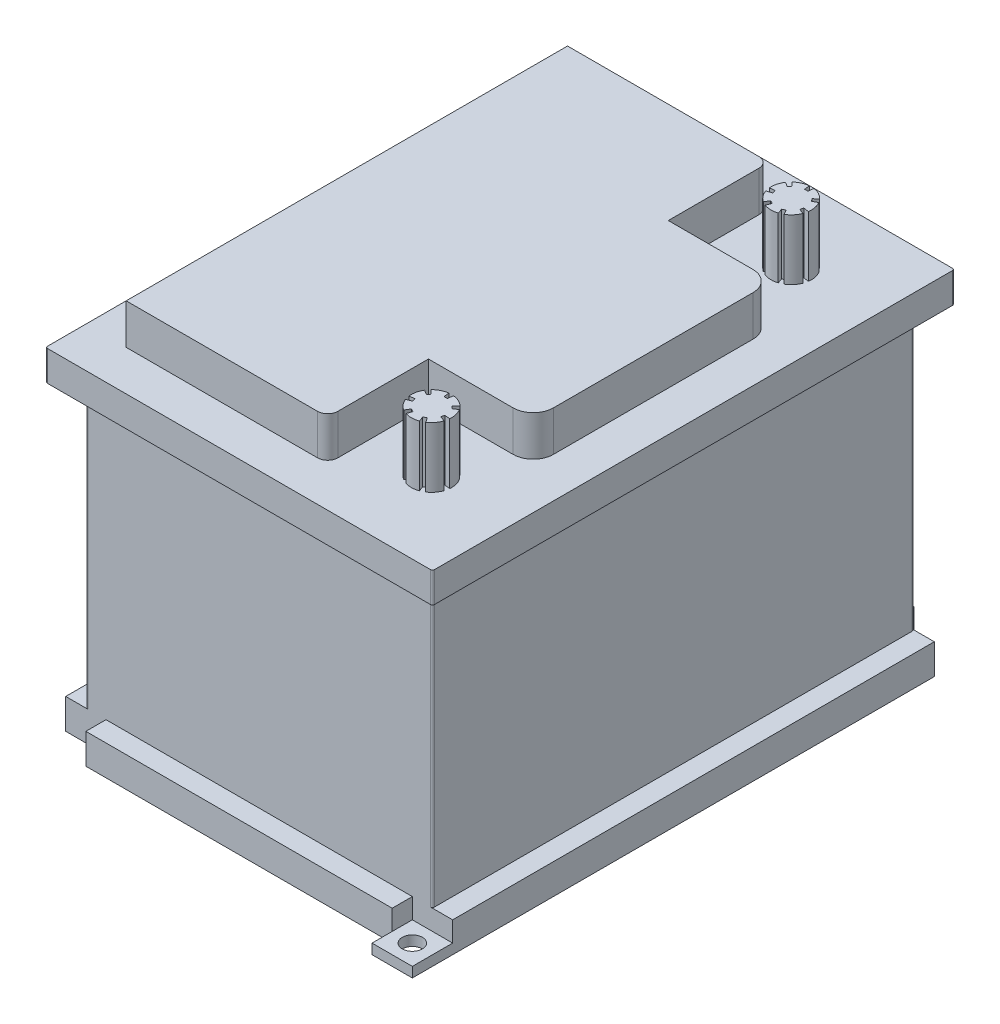
SolidWorks part; units mm, degrees
ref_plane "Front Plane" through (0, 0, 0) normal (0, 0, 1) x (1, 0, 0)
ref_plane "Top Plane" through (0, 0, 0) normal (0, 1, 0) x (1, 0, 0)
ref_plane "Right Plane" through (0, 0, 0) normal (1, 0, 0) x (0, 0, -1)
sketch "Sketch1" plane through (0, 0, 0) normal (0, 1, 0) x (1, 0, 0)
  line L3 (30.4274, 35.6969) -> (202.4274, 35.6969)
  line L4 (30.4274, 35.6969) -> (30.4274, -203.3031)
  line L5 (30.4274, -203.3031) -> (202.4274, -203.3031)
  line L6 (202.4274, 35.6969) -> (202.4274, -203.3031)
extrude "Boss-Extrude1" add sketch "Sketch1" along normal blind 190
sketch "Sketch2" plane through (0, 190, 0) normal (0, 1, 0) x (1, 0, 0)
  line L0 (192.4274, 35.6969) -> (40.4274, 35.6969)
  line L5 (202.4274, 35.6969) -> (30.4274, 35.6969) construction
  line L6 (30.4274, -193.3031) -> (30.4274, -203.3031)
  line L13 (40.4274, 25.6969) -> (192.4274, 25.6969)
  line L14 (40.4274, 25.6969) -> (40.4274, -193.3031)
  line L15 (40.4274, -193.3031) -> (192.4274, -193.3031)
  line L16 (192.4274, 25.6969) -> (192.4274, -193.3031)
  line L17 (30.4274, 35.6969) -> (202.4274, 35.6969)
  line L18 (30.4274, 35.6969) -> (30.4274, -203.3031)
  line L19 (30.4274, -203.3031) -> (202.4274, -203.3031)
  line L20 (202.4274, 35.6969) -> (202.4274, -203.3031)
  point P5 (116.4274, 35.6969)
  point P10 (30.4274, -198.3031)
  line M11 (30.4274, 35.6969) -> (30.4274, -203.3031)
  line M12 (30.4274, -203.3031) -> (202.4274, -203.3031)
  line M13 (202.4274, -203.3031) -> (202.4274, 35.6969)
  line M14 (202.4274, 35.6969) -> (30.4274, 35.6969)
extrude "Cut-Extrude1" cut sketch "Sketch2" against normal blind 20 contours L13 L16 L15 L14 M14 M11 M12 M13
sketch "Sketch3" plane through (0, 190, 0) normal (0, 1, 0) x (1, 0, 0)
  line L0 (40.4274, -193.3031) -> (192.4274, -193.3031) construction
  line L1 (40.4274, 25.6969) -> (140.4274, 25.6969) construction
  line L2 (40.4274, 25.6969) -> (40.4274, -193.3031) construction
  line L3 (40.4274, -193.3031) -> (140.4274, -193.3031) construction
  line L4 (140.4274, 25.6969) -> (140.4274, -193.3031) construction
  line L5 (140.4274, 25.6969) -> (140.4274, -24.3031)
  line L6 (140.4274, -193.3031) -> (140.4274, -143.3031)
  line L7 (140.4274, -143.3031) -> (192.4274, -143.3031)
  line L8 (192.4274, 25.6969) -> (192.4274, -193.3031) construction
  line L9 (192.4274, -143.3031) -> (192.4274, -24.3031)
  line L10 (192.4274, 25.6969) -> (192.4274, -193.3031) construction
  line L11 (192.4274, -24.3031) -> (140.4274, -24.3031)
  line L13 (40.4274, 25.6969) -> (192.4274, 25.6969)
  line L14 (40.4274, 25.6969) -> (40.4274, -193.3031)
  line L15 (40.4274, -193.3031) -> (192.4274, -193.3031)
  line L16 (192.4274, 25.6969) -> (192.4274, -193.3031)
  line M5 (192.4274, 25.6969) -> (40.4274, 25.6969)
  line M7 (40.4274, -193.3031) -> (192.4274, -193.3031)
  line M8 (192.4274, -193.3031) -> (192.4274, 25.6969)
extrude "Cut-Extrude2" cut sketch "Sketch3" against normal blind 20 contours L11 L5 M8 M5 | L7 L6 M7 M8
fillet "Fillet1" radius 10 1 edges at (192.4274, 180, 24.3031)
fillet "Fillet2" radius 10 1 edges at (192.4274, 180, 143.3031)
fillet "Fillet3" radius 5 1 edges at (140.4274, 180, 193.3031)
fillet "Fillet4" radius 5 1 edges at (140.4274, 180, -25.6969)
fillet "Fillet6" radius 1 1 edges at (30.4274, 85, 203.3031)
fillet "Fillet7" radius 1 1 edges at (202.4274, 85, 203.3031)
fillet "Fillet8" radius 1 1 edges at (202.4274, 85, -35.6969)
fillet "Fillet9" radius 1 1 edges at (30.4274, 85, -35.6969)
sketch "Sketch4" plane through (0, 170, 0) normal (0, 1, 0) x (1, 0, 0)
  line L1 (140.4274, -24.3031) -> (201.4274, -24.3031)
  line L2 (140.4274, -24.3031) -> (140.4274, 35.6969)
  line L3 (140.4274, 35.6969) -> (201.4274, 35.6969)
  line L4 (201.4274, -24.3031) -> (201.4274, 35.6969)
  line L5 (140.4274, -143.3031) -> (202.4274, -143.3031)
  line L6 (140.4274, -143.3031) -> (140.4274, -202.3031)
  line L7 (140.4274, -202.3031) -> (202.4274, -202.3031)
  line L8 (202.4274, -143.3031) -> (202.4274, -202.3031)
  circle A0 centre (171.4274, -172.8031) radius 10
  circle A1 centre (171.4274, 5.6969) radius 10
extrude "Boss-Extrude4" add sketch "Sketch4" along normal blind 30 contours A1 | A0
sketch "Sketch7" plane through (0, 200, 0) normal (0, 1, 0) x (1, 0, 0)
  line L0 (170.091, -162.8928) -> (170.4547, -165.5895)
  line L1 (170.4547, -165.5895) -> (172.1486, -165.5895)
  line L2 (172.1486, -165.5895) -> (172.4222, -162.8527)
  line L3 (178.3424, -165.5793) -> (176.4608, -167.5449)
  line L4 (177.5169, -168.8693) -> (179.8272, -167.3768)
  line L5 (176.4608, -167.5449) -> (177.5169, -168.8693)
  line L6 (181.3866, -173.7054) -> (178.6767, -173.4599)
  line L7 (178.2997, -175.1113) -> (180.907, -175.9871)
  line L8 (178.6767, -173.4599) -> (178.2997, -175.1113)
  line L9 (176.9314, -181.1521) -> (175.4337, -178.8803)
  line L10 (173.9076, -179.6152) -> (174.8485, -182.1997)
  line L11 (175.4337, -178.8803) -> (173.9076, -179.6152)
  line L12 (168.3316, -182.3118) -> (169.174, -179.7244)
  line L13 (167.6478, -178.9895) -> (166.2139, -181.3365)
  line L14 (169.174, -179.7244) -> (167.6478, -178.9895)
  line L15 (162.063, -176.3112) -> (164.6111, -175.3566)
  line L16 (164.2342, -173.7052) -> (161.5052, -174.0475)
  line L17 (164.6111, -175.3566) -> (164.2342, -173.7052)
  line L18 (162.846, -167.669) -> (165.1811, -169.066)
  line L19 (166.2372, -167.7416) -> (164.2681, -165.8214)
  line L20 (165.1811, -169.066) -> (166.2372, -167.7416)
  circle A0 centre (171.4274, -172.8031) radius 10
  point P33 (171.4274, -172.8031)
  circle M3 centre (171.4274, -172.8031) radius 10
  dimension "D1" = 7
extrude "Cut-Extrude8" cut sketch "Sketch7" against normal blind 30 contours L18 L20 L19 M3 | L15 L17 L16 M3 | L12 L14 L13 M3 | L9 L11 L10 M3 | L6 L8 L7 M3 | L3 L5 L4 M3 | L1 L2 L0 M3
ref_plane "Plane1" through (0, 0, 83.8031) normal (0, 0, 1) x (1, 0, 0)
sketch "Sketch8" plane through (0, 200, 0) normal (0, 1, 0) x (1, 0, 0)
  line L0 (170.5562, 15.6589) -> (170.7924, 12.9588)
  line L1 (170.7924, 12.9588) -> (172.4314, 12.9588)
  line L2 (172.4314, 12.9588) -> (172.7969, 15.6027)
  line L3 (177.731, 9.4397) -> (180.0259, 10.8024)
  line L4 (178.6728, 12.5892) -> (176.7091, 10.7212)
  line L5 (176.7091, 10.7212) -> (177.731, 9.4397)
  line L6 (178.2839, 3.1022) -> (180.7801, 2.1576)
  line L7 (181.3335, 4.3295) -> (178.6486, 4.7001)
  line L8 (178.6486, 4.7001) -> (178.2839, 3.1022)
  line L9 (173.6737, -1.2814) -> (174.4916, -3.8221)
  line L10 (176.5347, -2.9005) -> (175.1505, -0.5703)
  line L11 (175.1505, -0.5703) -> (173.6737, -1.2814)
  line L12 (167.3721, -0.4103) -> (165.8956, -2.6337)
  line L13 (167.89, -3.6565) -> (168.8488, -1.1214)
  line L14 (168.8488, -1.1214) -> (167.3721, -0.4103)
  line L15 (164.1242, 5.0598) -> (161.4653, 4.8278)
  line L16 (161.9091, 2.6308) -> (164.4889, 3.4618)
  line L17 (164.4889, 3.4618) -> (164.1242, 5.0598)
  line L18 (166.3758, 11.0096) -> (164.5366, 12.9438)
  line L19 (163.0957, 11.227) -> (165.3539, 9.7281)
  line L20 (165.3539, 9.7281) -> (166.3758, 11.0096)
  circle A0 centre (171.4274, 5.6969) radius 10
  point P33 (171.4274, 5.6969)
  circle M2 centre (171.4274, 5.6969) radius 10
  dimension "D1" = 7
extrude "Cut-Extrude9" cut sketch "Sketch8" against normal blind 30 contours L19 L20 L18 M2 | L1 L2 L0 M2 | L4 L5 L3 M2 | L7 L8 L6 M2 | L16 L17 L15 M2 | L13 L14 L12 M2 | L10 L11 L9 M2
sketch "Sketch9" plane through (0, 170, 0) normal (0, 1, 0) x (1, 0, 0)
  line L1 (31.4274, 35.6969) -> (201.4274, 35.6969)
  line L2 (30.4274, 34.6969) -> (30.4274, -202.3031)
  line L3 (31.4274, -203.3031) -> (201.4274, -203.3031)
  line L4 (202.4274, 34.6969) -> (202.4274, -202.3031)
  line L5 (21.4274, 45.6969) -> (211.4274, 45.6969)
  line L6 (20.4274, 44.6969) -> (20.4274, -212.3031)
  line L7 (21.4274, -213.3031) -> (211.4274, -213.3031)
  line L8 (212.4274, 44.6969) -> (212.4274, -212.3031)
  arc A0 (21.4274, 45.6969) -> (20.4274, 44.6969) centre (21.4274, 44.6969) ccw
  arc A1 (211.4274, 45.6969) -> (212.4274, 44.6969) centre (211.4274, 44.6969) cw
  arc A2 (20.4274, -212.3031) -> (21.4274, -213.3031) centre (21.4274, -212.3031) ccw
  arc A3 (211.4274, -213.3031) -> (212.4274, -212.3031) centre (211.4274, -212.3031) ccw
  arc A4 (201.4274, 35.6969) -> (202.4274, 34.6969) centre (201.4274, 34.6969) cw
  arc A5 (31.4274, 35.6969) -> (30.4274, 34.6969) centre (31.4274, 34.6969) ccw
  arc A6 (30.4274, -202.3031) -> (31.4274, -203.3031) centre (31.4274, -202.3031) ccw
  arc A7 (201.4274, -203.3031) -> (202.4274, -202.3031) centre (201.4274, -202.3031) ccw
  dimension "D1" = 1
  dimension "D2" = 1
  dimension "D3" = 1
  dimension "D4" = 1
extrude "Boss-Extrude5" add sketch "Sketch9" against normal blind 15
ref_plane "Plane2" through (0, 85, 0) normal (0, 1, 0) x (1, 0, 0)
mirror "Mirror2" about plane through (0, 85, 0) normal (0, 1, 0) of "Boss-Extrude5"
sketch "Sketch11" plane through (0, 15, 0) normal (0, 1, 0) x (1, 0, 0)
  line L13 (20.4274, -213.3031) -> (40.4274, -213.3031)
  line L14 (20.4274, -213.3031) -> (20.4274, -203.3031)
  line L15 (20.4274, -203.3031) -> (40.4274, -203.3031)
  line L16 (40.4274, -213.3031) -> (40.4274, -203.3031)
  line L17 (212.4274, -213.3031) -> (192.4274, -213.3031)
  line L18 (212.4274, -213.3031) -> (212.4274, -203.3031)
  line L19 (212.4274, -203.3031) -> (192.4274, -203.3031)
  line L20 (192.4274, -213.3031) -> (192.4274, -203.3031)
  line L21 (212.4274, 45.6969) -> (192.4274, 45.6969)
  line L22 (212.4274, 45.6969) -> (212.4274, 35.6969)
  line L23 (212.4274, 35.6969) -> (192.4274, 35.6969)
  line L24 (192.4274, 45.6969) -> (192.4274, 35.6969)
  line L25 (20.4274, 45.6969) -> (40.4274, 45.6969)
  line L26 (20.4274, 45.6969) -> (20.4274, 35.6969)
  line L27 (20.4274, 35.6969) -> (40.4274, 35.6969)
  line L28 (40.4274, 45.6969) -> (40.4274, 35.6969)
extrude "Cut-Extrude11" cut sketch "Sketch11" against normal blind 15
sketch "Sketch12" plane through (0, 0, 203.3031) normal (0, 0, 1) x (1, 0, 0)
  line L0 (192.4274, 0) -> (192.4274, 15) construction
  line L1 (212.4274, 0) -> (192.4274, 0)
  line L2 (212.4274, 0) -> (212.4274, 5)
  line L3 (212.4274, 5) -> (192.4274, 5)
  line L4 (192.4274, 0) -> (192.4274, 5)
extrude "Boss-Extrude6" add sketch "Sketch12" along normal blind 20
sketch "Sketch13" plane through (0, 5, 0) normal (0, 1, 0) x (1, 0, 0)
  circle A0 centre (202.4274, -213.3031) radius 5
extrude "Cut-Extrude12" cut sketch "Sketch13" against normal blind 20
sketch "Sketch14" plane through (0, 0, -35.6969) normal (0, 0, -1) x (-1, 0, 0)
  line L0 (-40.4274, 0) -> (-40.4274, 15) construction
  line L1 (-20.4274, 0) -> (-40.4274, 0)
  line L2 (-20.4274, 0) -> (-20.4274, 5)
  line L3 (-20.4274, 5) -> (-40.4274, 5)
  line L4 (-40.4274, 0) -> (-40.4274, 5)
extrude "Boss-Extrude7" add sketch "Sketch14" along normal blind 20
sketch "Sketch15" plane through (0, 5, 0) normal (0, 1, 0) x (1, 0, 0)
  circle A0 centre (30.4274, 45.6969) radius 5
extrude "Cut-Extrude13" cut sketch "Sketch15" against normal blind 20
